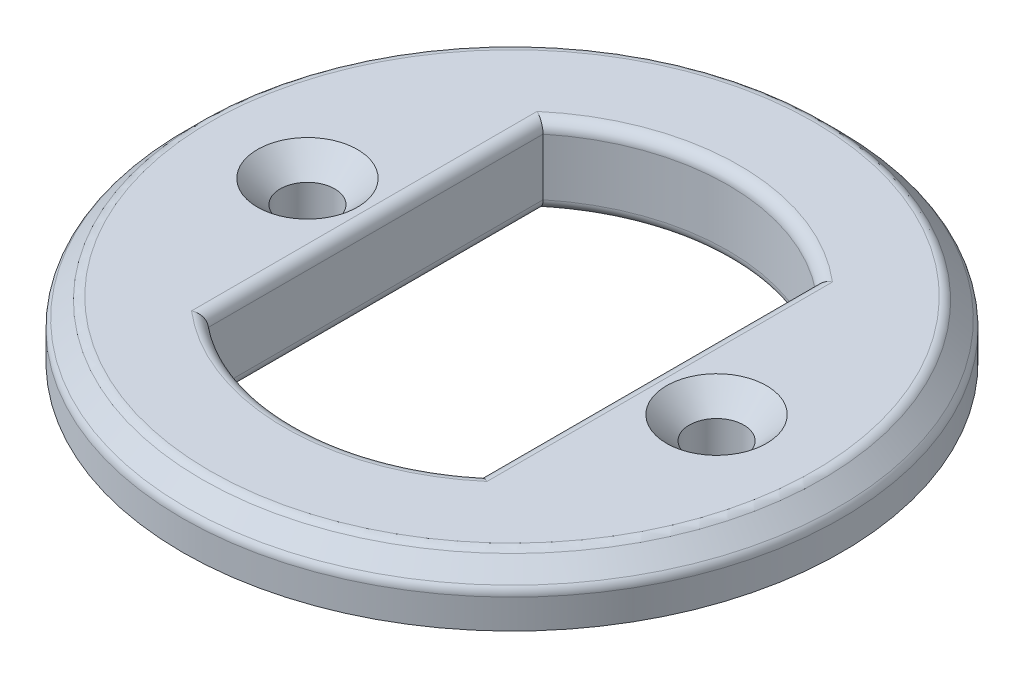
SolidWorks part; units mm, degrees
ref_plane "Plan de face" through (0, 0, 0) normal (0, 0, 1) x (1, 0, 0)
ref_plane "Plan de dessus" through (0, 0, 0) normal (0, 1, 0) x (1, 0, 0)
ref_plane "Plan de droite" through (0, 0, 0) normal (1, 0, 0) x (0, 0, -1)
sketch "Esquisse1" plane through (0, 0, 0) normal (0, 0, 1) x (1, 0, 0)
  line L0 (0, -5.3474) -> (0, 12.7) construction
  line L1 (12, 0) -> (12, 1)
  line L2 (12, 1) -> (14.5, 1)
  line L3 (14.5, 1) -> (14.5, 2.5)
  line L4 (14.5, 2.5) -> (13.5, 3.5)
  line L5 (13.5, 3.5) -> (0, 3.5)
  line L6 (12, 0) -> (0, 0)
  line L7 (0, 0) -> (0, 3.5)
  dimension "D1" = 12
  dimension "D2" = 14.5
  dimension "D3" = 1
  dimension "D4" = 1.5
  dimension "D5" = 1
  dimension "D6" = 1
revolve "Révolution1" add sketch "Esquisse1" angle 360 about L0
sketch "Esquisse2" plane through (0, 3.5, 0) normal (0, 1, 0) x (1, 0, 0)
  line L0 (-6, -7.3655) -> (-6, 7.3655)
  line L1 (6, 7.3655) -> (6, -7.3655)
  arc A0 (6, 7.3655) -> (-6, 7.3655) centre (0, 0) ccw construction
  arc A1 (6, 7.3655) -> (-6, 7.3655) centre (0, 0) ccw
  arc A2 (-6, -7.3655) -> (6, -7.3655) centre (0, 0) ccw construction
  arc A3 (-6, -7.3655) -> (6, -7.3655) centre (0, 0) ccw
  dimension "D1" = 19
  dimension "D2" = 6
  dimension "D3" = 12
extrude "Enlèv. mat.-Extru.1" cut sketch "Esquisse2" against normal through all
fillet "Congé1" radius 0.5 10 edges at (0, 3.5, -13.5) (6, 3.5, 0) (0, 3.5, -9.5) (-6, 3.5, 0) (0, 3.5, 9.5) (0, 2.5, -14.5) (6, 0, 0) (0, 0, 9.5) (-6, 0, 0) (0, 0, -9.5)
sketch "Esquisse4" plane through (0, 3.5, 0) normal (0, 1, 0) x (-1, 0, 0)
  line L0 (12.0359, 0) -> (-12.494, 0) construction
  circle A0 centre (0, 0) radius 9 construction
  dimension "D1" = 18
hole_wizard "Fraisage pour vis à tête fraisée M21" positions "Esquisse3D2" profile "Esquisse5" countersink size "M2" standard "ISO" end condition through all
sketch3d "Esquisse3D2"
  line L0 (-12.0359, 3.5, 0) -> (12.494, 3.5, 0) construction
  circle A0 centre (0, 3.5, 0) radius 9 construction
  point P0 (-9, 3.5, 0)
  point P6 (0, 12.5, 0)
  point P7 (9, 3.5, 0)
sketch "Esquisse5" plane through (-9, 3.5, 0) normal (1, 0, 0) x (0, 0, 1)
  line L0 (0, 0) -> (0, 3.5)
  line L1 (0, 3.5) -> (1.2, 3.5)
  line L2 (1.2, 3.5) -> (1.2, 1)
  line L3 (1.2, 1) -> (2.2, 0)
  line L5 (2.2, 0) -> (0, 0)
  line L6 (-1.2, 1) -> (-2.2, 0) construction
  line L11 (0, -6.35) -> (0, 107.95) construction
  dimension "Diamètre du perçage jusqu'au prochain" = 2.4
  dimension "Profondeur du perçage jusqu'au prochain" = 3.5
  dimension "Diamètre du fraisage entrant" = 4.4
  dimension "Angle du fraisage entrant" = 90
